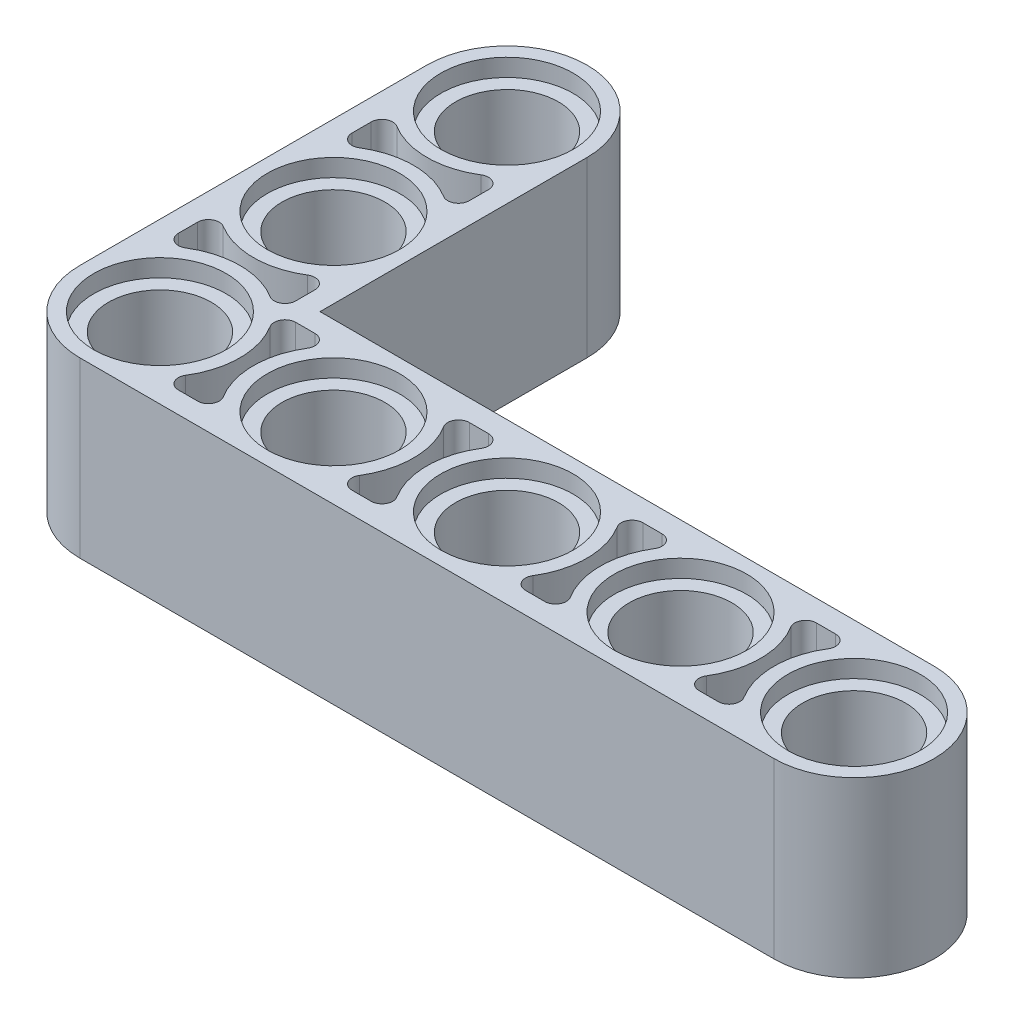
SolidWorks part; units mm, degrees
ref_plane "Front Plane" through (0, 0, 0) normal (0, 0, 1) x (1, 0, 0)
ref_plane "Top Plane" through (0, 0, 0) normal (0, 1, 0) x (1, 0, 0)
ref_plane "Right Plane" through (0, 0, 0) normal (1, 0, 0) x (0, 0, -1)
ref_plane "Plane1" through (0, 4.0325, 0) normal (0, 1, 0) x (1, 0, 0)
sketch "Sketch1" plane through (0, 4.0325, 0) normal (0, 1, 0) x (1, 0, 0)
  line L0 (0, 3.72) -> (-28.54, 3.72)
  line L1 (-28.54, 3.72) -> (-28.54, 16.13)
  line L2 (-35.98, 16.13) -> (-35.98, -3.72)
  line L3 (-35.98, -3.72) -> (0, -3.72)
  arc A0 (-28.54, 16.13) -> (-35.98, 16.13) centre (-32.26, 16.13) ccw
  arc A1 (0, -3.72) -> (0, 3.72) centre (0, 0) ccw
extrude "Boss-Extrude1" add sketch "Sketch1" against normal blind 8.065
sketch "Sketch2" plane through (0, 4.0325, 0) normal (0, 1, 0) x (-1, 0, 0)
  line L0 (3.5855, -2.7254) -> (4.4795, -2.7254)
  line L1 (4.4795, 2.7254) -> (3.5855, 2.7254)
  arc A0 (3.1607, 1.9618) -> (3.1607, -1.9618) centre (0, 0) cw
  arc A1 (3.1607, -1.9618) -> (3.5855, -2.7254) centre (3.5855, -2.2254) ccw
  arc A2 (4.4795, -2.7254) -> (4.9043, -1.9618) centre (4.4795, -2.2254) ccw
  arc A3 (4.9043, -1.9618) -> (4.9043, 1.9618) centre (8.065, 0) cw
  arc A4 (4.9043, 1.9618) -> (4.4795, 2.7254) centre (4.4795, 2.2254) ccw
  arc A5 (3.5855, 2.7254) -> (3.1607, 1.9618) centre (3.5855, 2.2254) ccw
extrude "Cut-Extrude1" cut sketch "Sketch2" against normal blind 3
sketch "Sketch3" plane through (0, 4.0325, 0) normal (0, 1, 0) x (-1, 0, 0)
  line L0 (11.6505, -2.7254) -> (12.5445, -2.7254)
  line L1 (12.5445, 2.7254) -> (11.6505, 2.7254)
  arc A0 (11.6505, 2.7254) -> (11.2257, 1.9618) centre (11.6505, 2.2254) ccw
  arc A1 (11.2257, 1.9618) -> (11.2257, -1.9618) centre (8.065, 0) cw
  arc A2 (11.2257, -1.9618) -> (11.6505, -2.7254) centre (11.6505, -2.2254) ccw
  arc A3 (12.5445, -2.7254) -> (12.9693, -1.9618) centre (12.5445, -2.2254) ccw
  arc A4 (12.9693, -1.9618) -> (12.9693, 1.9618) centre (16.13, 0) cw
  arc A5 (12.9693, 1.9618) -> (12.5445, 2.7254) centre (12.5445, 2.2254) ccw
extrude "Cut-Extrude2" cut sketch "Sketch3" against normal blind 3
sketch "Sketch4" plane through (0, 4.0325, 0) normal (0, 1, 0) x (-1, 0, 0)
  line L0 (19.7155, -2.7254) -> (20.6095, -2.7254)
  line L1 (20.6095, 2.7254) -> (19.7155, 2.7254)
  arc A0 (19.2907, 1.9618) -> (19.2907, -1.9618) centre (16.13, 0) cw
  arc A1 (19.2907, -1.9618) -> (19.7155, -2.7254) centre (19.7155, -2.2254) ccw
  arc A2 (20.6095, -2.7254) -> (21.0343, -1.9618) centre (20.6095, -2.2254) ccw
  arc A3 (21.0343, -1.9618) -> (21.0343, 1.9618) centre (24.195, 0) cw
  arc A4 (21.0343, 1.9618) -> (20.6095, 2.7254) centre (20.6095, 2.2254) ccw
  arc A5 (19.7155, 2.7254) -> (19.2907, 1.9618) centre (19.7155, 2.2254) ccw
extrude "Cut-Extrude3" cut sketch "Sketch4" against normal blind 3
sketch "Sketch5" plane through (0, 4.0325, 0) normal (0, 1, 0) x (-1, 0, 0)
  line L0 (27.7805, -2.7254) -> (28.6745, -2.7254)
  line L1 (28.6745, 2.7254) -> (27.7805, 2.7254)
  arc A0 (27.7805, 2.7254) -> (27.3557, 1.9618) centre (27.7805, 2.2254) ccw
  arc A1 (27.3557, 1.9618) -> (27.3557, -1.9618) centre (24.195, 0) cw
  arc A2 (27.3557, -1.9618) -> (27.7805, -2.7254) centre (27.7805, -2.2254) ccw
  arc A3 (28.6745, -2.7254) -> (29.0993, -1.9618) centre (28.6745, -2.2254) ccw
  arc A4 (29.0993, -1.9618) -> (29.0993, 1.9618) centre (32.26, 0) cw
  arc A5 (29.0993, 1.9618) -> (28.6745, 2.7254) centre (28.6745, 2.2254) ccw
extrude "Cut-Extrude4" cut sketch "Sketch5" against normal blind 3
sketch "Sketch6" plane through (0, 4.0325, 0) normal (0, 1, 0) x (-1, 0, 0)
  line L0 (29.5346, -3.5855) -> (29.5346, -4.4795)
  line L1 (34.9854, -4.4795) -> (34.9854, -3.5855)
  arc A0 (34.2218, -3.1607) -> (30.2982, -3.1607) centre (32.26, 0) cw
  arc A1 (30.2982, -3.1607) -> (29.5346, -3.5855) centre (30.0346, -3.5855) ccw
  arc A2 (29.5346, -4.4795) -> (30.2982, -4.9043) centre (30.0346, -4.4795) ccw
  arc A3 (30.2982, -4.9043) -> (34.2218, -4.9043) centre (32.26, -8.065) cw
  arc A4 (34.2218, -4.9043) -> (34.9854, -4.4795) centre (34.4854, -4.4795) ccw
  arc A5 (34.9854, -3.5855) -> (34.2218, -3.1607) centre (34.4854, -3.5855) ccw
extrude "Cut-Extrude5" cut sketch "Sketch6" against normal blind 3
sketch "Sketch7" plane through (0, 4.0325, 0) normal (0, 1, 0) x (-1, 0, 0)
  line L0 (29.5346, -11.6505) -> (29.5346, -12.5445)
  line L1 (34.9854, -12.5445) -> (34.9854, -11.6505)
  arc A0 (34.9854, -11.6505) -> (34.2218, -11.2257) centre (34.4854, -11.6505) ccw
  arc A1 (34.2218, -11.2257) -> (30.2982, -11.2257) centre (32.26, -8.065) cw
  arc A2 (30.2982, -11.2257) -> (29.5346, -11.6505) centre (30.0346, -11.6505) ccw
  arc A3 (29.5346, -12.5445) -> (30.2982, -12.9693) centre (30.0346, -12.5445) ccw
  arc A4 (30.2982, -12.9693) -> (34.2218, -12.9693) centre (32.26, -16.13) cw
  arc A5 (34.2218, -12.9693) -> (34.9854, -12.5445) centre (34.4854, -12.5445) ccw
extrude "Cut-Extrude6" cut sketch "Sketch7" against normal blind 3
sketch "Sketch8" plane through (0, -4.0325, 0) normal (0, -1, 0) x (1, 0, 0)
  line L0 (-4.4795, -2.7254) -> (-3.5855, -2.7254)
  line L1 (-3.5855, 2.7254) -> (-4.4795, 2.7254)
  arc A0 (-3.5855, -2.7254) -> (-3.1607, -1.9618) centre (-3.5855, -2.2254) ccw
  arc A1 (-3.1607, -1.9618) -> (-3.1607, 1.9618) centre (0, 0) cw
  arc A2 (-3.1607, 1.9618) -> (-3.5855, 2.7254) centre (-3.5855, 2.2254) ccw
  arc A3 (-4.4795, 2.7254) -> (-4.9043, 1.9618) centre (-4.4795, 2.2254) ccw
  arc A4 (-4.9043, 1.9618) -> (-4.9043, -1.9618) centre (-8.065, 0) cw
  arc A5 (-4.9043, -1.9618) -> (-4.4795, -2.7254) centre (-4.4795, -2.2254) ccw
extrude "Cut-Extrude7" cut sketch "Sketch8" against normal blind 3
sketch "Sketch9" plane through (0, -4.0325, 0) normal (0, -1, 0) x (1, 0, 0)
  line L0 (-11.6505, 2.7254) -> (-12.5445, 2.7254)
  line L1 (-12.5445, -2.7254) -> (-11.6505, -2.7254)
  arc A0 (-11.6505, -2.7254) -> (-11.2257, -1.9618) centre (-11.6505, -2.2254) ccw
  arc A1 (-11.2257, -1.9618) -> (-11.2257, 1.9618) centre (-8.065, 0) cw
  arc A2 (-11.2257, 1.9618) -> (-11.6505, 2.7254) centre (-11.6505, 2.2254) ccw
  arc A3 (-12.5445, 2.7254) -> (-12.9693, 1.9618) centre (-12.5445, 2.2254) ccw
  arc A4 (-12.9693, 1.9618) -> (-12.9693, -1.9618) centre (-16.13, 0) cw
  arc A5 (-12.9693, -1.9618) -> (-12.5445, -2.7254) centre (-12.5445, -2.2254) ccw
extrude "Cut-Extrude8" cut sketch "Sketch9" against normal blind 3
sketch "Sketch10" plane through (0, -4.0325, 0) normal (0, -1, 0) x (1, 0, 0)
  line L0 (-20.6095, -2.7254) -> (-19.7155, -2.7254)
  line L1 (-19.7155, 2.7254) -> (-20.6095, 2.7254)
  arc A0 (-19.7155, -2.7254) -> (-19.2907, -1.9618) centre (-19.7155, -2.2254) ccw
  arc A1 (-19.2907, -1.9618) -> (-19.2907, 1.9618) centre (-16.13, 0) cw
  arc A2 (-19.2907, 1.9618) -> (-19.7155, 2.7254) centre (-19.7155, 2.2254) ccw
  arc A3 (-20.6095, 2.7254) -> (-21.0343, 1.9618) centre (-20.6095, 2.2254) ccw
  arc A4 (-21.0343, 1.9618) -> (-21.0343, -1.9618) centre (-24.195, 0) cw
  arc A5 (-21.0343, -1.9618) -> (-20.6095, -2.7254) centre (-20.6095, -2.2254) ccw
extrude "Cut-Extrude9" cut sketch "Sketch10" against normal blind 3
sketch "Sketch11" plane through (0, -4.0325, 0) normal (0, -1, 0) x (1, 0, 0)
  line L0 (-27.7805, 2.7254) -> (-28.6745, 2.7254)
  line L1 (-28.6745, -2.7254) -> (-27.7805, -2.7254)
  arc A0 (-27.7805, -2.7254) -> (-27.3557, -1.9618) centre (-27.7805, -2.2254) ccw
  arc A1 (-27.3557, -1.9618) -> (-27.3557, 1.9618) centre (-24.195, 0) cw
  arc A2 (-27.3557, 1.9618) -> (-27.7805, 2.7254) centre (-27.7805, 2.2254) ccw
  arc A3 (-28.6745, 2.7254) -> (-29.0993, 1.9618) centre (-28.6745, 2.2254) ccw
  arc A4 (-29.0993, 1.9618) -> (-29.0993, -1.9618) centre (-32.26, 0) cw
  arc A5 (-29.0993, -1.9618) -> (-28.6745, -2.7254) centre (-28.6745, -2.2254) ccw
extrude "Cut-Extrude10" cut sketch "Sketch11" against normal blind 3
sketch "Sketch12" plane through (0, -4.0325, 0) normal (0, -1, 0) x (1, 0, 0)
  line L0 (-29.5346, -4.4795) -> (-29.5346, -3.5855)
  line L1 (-34.9854, -3.5855) -> (-34.9854, -4.4795)
  arc A0 (-29.5346, -3.5855) -> (-30.2982, -3.1607) centre (-30.0346, -3.5855) ccw
  arc A1 (-30.2982, -3.1607) -> (-34.2218, -3.1607) centre (-32.26, 0) cw
  arc A2 (-34.2218, -3.1607) -> (-34.9854, -3.5855) centre (-34.4854, -3.5855) ccw
  arc A3 (-34.9854, -4.4795) -> (-34.2218, -4.9043) centre (-34.4854, -4.4795) ccw
  arc A4 (-34.2218, -4.9043) -> (-30.2982, -4.9043) centre (-32.26, -8.065) cw
  arc A5 (-30.2982, -4.9043) -> (-29.5346, -4.4795) centre (-30.0346, -4.4795) ccw
extrude "Cut-Extrude11" cut sketch "Sketch12" against normal blind 3
sketch "Sketch13" plane through (0, -4.0325, 0) normal (0, -1, 0) x (1, 0, 0)
  line L0 (-34.9854, -11.6505) -> (-34.9854, -12.5445)
  line L1 (-29.5346, -12.5445) -> (-29.5346, -11.6505)
  arc A0 (-29.5346, -11.6505) -> (-30.2982, -11.2257) centre (-30.0346, -11.6505) ccw
  arc A1 (-30.2982, -11.2257) -> (-34.2218, -11.2257) centre (-32.26, -8.065) cw
  arc A2 (-34.2218, -11.2257) -> (-34.9854, -11.6505) centre (-34.4854, -11.6505) ccw
  arc A3 (-34.9854, -12.5445) -> (-34.2218, -12.9693) centre (-34.4854, -12.5445) ccw
  arc A4 (-34.2218, -12.9693) -> (-30.2982, -12.9693) centre (-32.26, -16.13) cw
  arc A5 (-30.2982, -12.9693) -> (-29.5346, -12.5445) centre (-30.0346, -12.5445) ccw
extrude "Cut-Extrude12" cut sketch "Sketch13" against normal blind 3
ref_plane "Plane2" through (0, 0, 0) normal (0, 0, -1) x (-1, 0, 0)
sketch "Sketch14" plane through (0, 0, 0) normal (0, 0, -1) x (-1, 0, 0)
  line L0 (-3.075, -4.0325) -> (0, -4.0325)
  line L1 (0, -4.0325) -> (0, 4.0325)
  line L2 (0, 4.0325) -> (-3.075, 4.0325)
  line L3 (-3.075, 4.0325) -> (-3.075, 3.2175)
  line L4 (-3.075, 3.2175) -> (-2.39, 3.2175)
  line L5 (-2.39, 3.2175) -> (-2.39, -3.2175)
  line L6 (-2.39, -3.2175) -> (-3.075, -3.2175)
  line L7 (-3.075, -3.2175) -> (-3.075, -4.0325)
  line L8 (0, -4.0325) -> (0, 4.0325) construction
revolve "Cut-Revolve1" cut sketch "Sketch14" angle 360 about L8
sketch "Sketch15" plane through (0, 0, 0) normal (0, 0, -1) x (-1, 0, 0)
  line L0 (4.99, -4.0325) -> (8.065, -4.0325)
  line L1 (8.065, -4.0325) -> (8.065, 4.0325)
  line L2 (8.065, 4.0325) -> (4.99, 4.0325)
  line L3 (4.99, 4.0325) -> (4.99, 3.2175)
  line L4 (4.99, 3.2175) -> (5.675, 3.2175)
  line L5 (5.675, 3.2175) -> (5.675, -3.2175)
  line L6 (5.675, -3.2175) -> (4.99, -3.2175)
  line L7 (4.99, -3.2175) -> (4.99, -4.0325)
  line L8 (8.065, -4.0325) -> (8.065, 4.0325) construction
revolve "Cut-Revolve2" cut sketch "Sketch15" angle 360 about L8
sketch "Sketch16" plane through (0, 0, 0) normal (0, 0, -1) x (-1, 0, 0)
  line L0 (13.055, -4.0325) -> (16.13, -4.0325)
  line L1 (16.13, -4.0325) -> (16.13, 4.0325)
  line L2 (16.13, 4.0325) -> (13.055, 4.0325)
  line L3 (13.055, 4.0325) -> (13.055, 3.2175)
  line L4 (13.055, 3.2175) -> (13.74, 3.2175)
  line L5 (13.74, 3.2175) -> (13.74, -3.2175)
  line L6 (13.74, -3.2175) -> (13.055, -3.2175)
  line L7 (13.055, -3.2175) -> (13.055, -4.0325)
  line L8 (16.13, -4.0325) -> (16.13, 4.0325) construction
revolve "Cut-Revolve3" cut sketch "Sketch16" angle 360 about L8
sketch "Sketch17" plane through (0, 0, 0) normal (0, 0, -1) x (-1, 0, 0)
  line L0 (21.12, -4.0325) -> (24.195, -4.0325)
  line L1 (24.195, -4.0325) -> (24.195, 4.0325)
  line L2 (24.195, 4.0325) -> (21.12, 4.0325)
  line L3 (21.12, 4.0325) -> (21.12, 3.2175)
  line L4 (21.12, 3.2175) -> (21.805, 3.2175)
  line L5 (21.805, 3.2175) -> (21.805, -3.2175)
  line L6 (21.805, -3.2175) -> (21.12, -3.2175)
  line L7 (21.12, -3.2175) -> (21.12, -4.0325)
  line L8 (24.195, -4.0325) -> (24.195, 4.0325) construction
revolve "Cut-Revolve4" cut sketch "Sketch17" angle 360 about L8
sketch "Sketch18" plane through (0, 0, 0) normal (0, 0, -1) x (-1, 0, 0)
  line L0 (29.185, -4.0325) -> (32.26, -4.0325)
  line L1 (32.26, -4.0325) -> (32.26, 4.0325)
  line L2 (32.26, 4.0325) -> (29.185, 4.0325)
  line L3 (29.185, 4.0325) -> (29.185, 3.2175)
  line L4 (29.185, 3.2175) -> (29.87, 3.2175)
  line L5 (29.87, 3.2175) -> (29.87, -3.2175)
  line L6 (29.87, -3.2175) -> (29.185, -3.2175)
  line L7 (29.185, -3.2175) -> (29.185, -4.0325)
  line L8 (32.26, -4.0325) -> (32.26, 4.0325) construction
revolve "Cut-Revolve5" cut sketch "Sketch18" angle 360 about L8
ref_plane "Plane3" through (0, 0, -8.065) normal (0, 0, -1) x (-1, 0, 0)
sketch "Sketch19" plane through (0, 0, -8.065) normal (0, 0, -1) x (-1, 0, 0)
  line L0 (29.185, -4.0325) -> (32.26, -4.0325)
  line L1 (32.26, -4.0325) -> (32.26, 4.0325)
  line L2 (32.26, 4.0325) -> (29.185, 4.0325)
  line L3 (29.185, 4.0325) -> (29.185, 3.2175)
  line L4 (29.185, 3.2175) -> (29.87, 3.2175)
  line L5 (29.87, 3.2175) -> (29.87, -3.2175)
  line L6 (29.87, -3.2175) -> (29.185, -3.2175)
  line L7 (29.185, -3.2175) -> (29.185, -4.0325)
  line L8 (32.26, -4.0325) -> (32.26, 4.0325) construction
revolve "Cut-Revolve6" cut sketch "Sketch19" angle 360 about L8
ref_plane "Plane4" through (0, 0, -16.13) normal (0, 0, -1) x (-1, 0, 0)
sketch "Sketch20" plane through (0, 0, -16.13) normal (0, 0, -1) x (-1, 0, 0)
  line L0 (29.185, -4.0325) -> (32.26, -4.0325)
  line L1 (32.26, -4.0325) -> (32.26, 4.0325)
  line L2 (32.26, 4.0325) -> (29.185, 4.0325)
  line L3 (29.185, 4.0325) -> (29.185, 3.2175)
  line L4 (29.185, 3.2175) -> (29.87, 3.2175)
  line L5 (29.87, 3.2175) -> (29.87, -3.2175)
  line L6 (29.87, -3.2175) -> (29.185, -3.2175)
  line L7 (29.185, -3.2175) -> (29.185, -4.0325)
  line L8 (32.26, -4.0325) -> (32.26, 4.0325) construction
revolve "Cut-Revolve7" cut sketch "Sketch20" angle 360 about L8
fillet "Fillet1" radius 3.72 1 edges at (-35.98, 0, 3.72)
